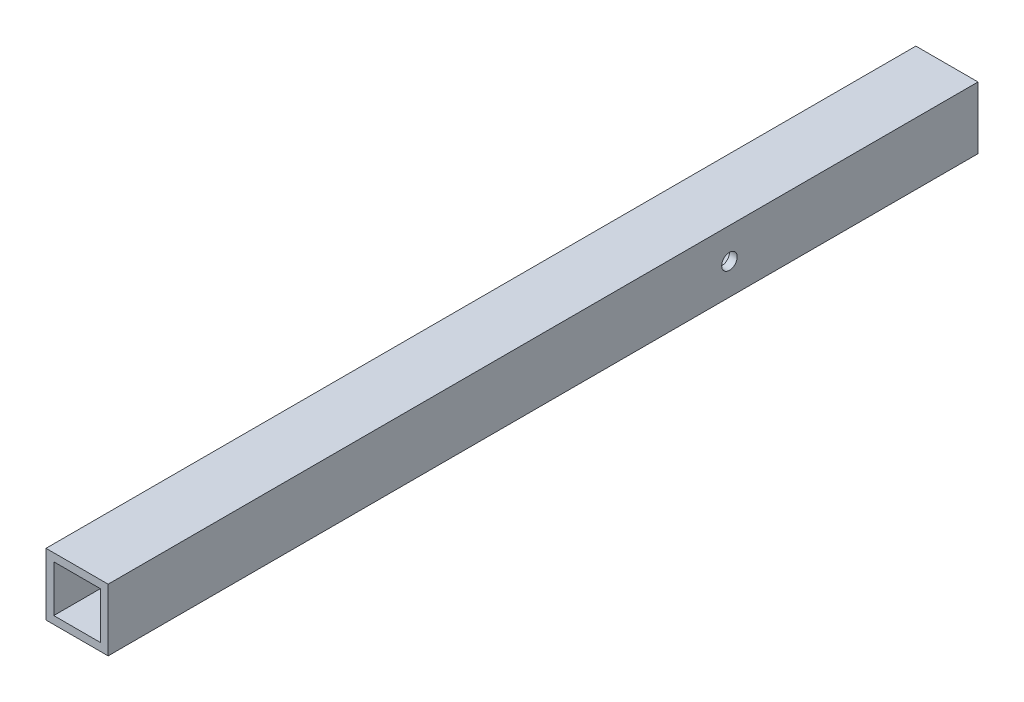
SolidWorks part; units mm, degrees
ref_plane "Front Plane" through (0, 0, 0) normal (0, 0, 1) x (1, 0, 0)
ref_plane "Top Plane" through (0, 0, 0) normal (0, 1, 0) x (1, 0, 0)
ref_plane "Right Plane" through (0, 0, 0) normal (1, 0, 0) x (0, 0, -1)
sketch "Sketch1" plane through (0, 0, 0) normal (0, 0, 1) x (1, 0, 0)
  line L1 (0, 0) -> (25.4, 0)
  line L2 (0, 0) -> (0, 25.4)
  line L3 (0, 25.4) -> (25.4, 25.4)
  line L4 (25.4, 0) -> (25.4, 25.4)
  line L5 (22.225, 22.225) -> (3.175, 22.225)
  line L6 (22.225, 22.225) -> (22.225, 3.175)
  line L7 (22.225, 3.175) -> (3.175, 3.175)
  line L8 (3.175, 22.225) -> (3.175, 3.175)
  dimension "D1" = 25.4
  dimension "D2" = 25.4
  dimension "D3" = 3.175
  dimension "D4" = 3.175
  dimension "D5" = 3.175
  dimension "D6" = 3.175
extrude "Boss-Extrude1" add sketch "Sketch1" along normal blind 355.6
sketch "Sketch2" plane through (0, 0, 0) normal (-1, 0, 0) x (0, 0, 1)
  line L0 (0, 25.4) -> (0, 0) construction
  circle A0 centre (101.6, 12.7) radius 3.175
  dimension "D1" = 6.35
  dimension "D2" = 101.6
extrude "Cut-Extrude1" cut sketch "Sketch2" against normal through all
